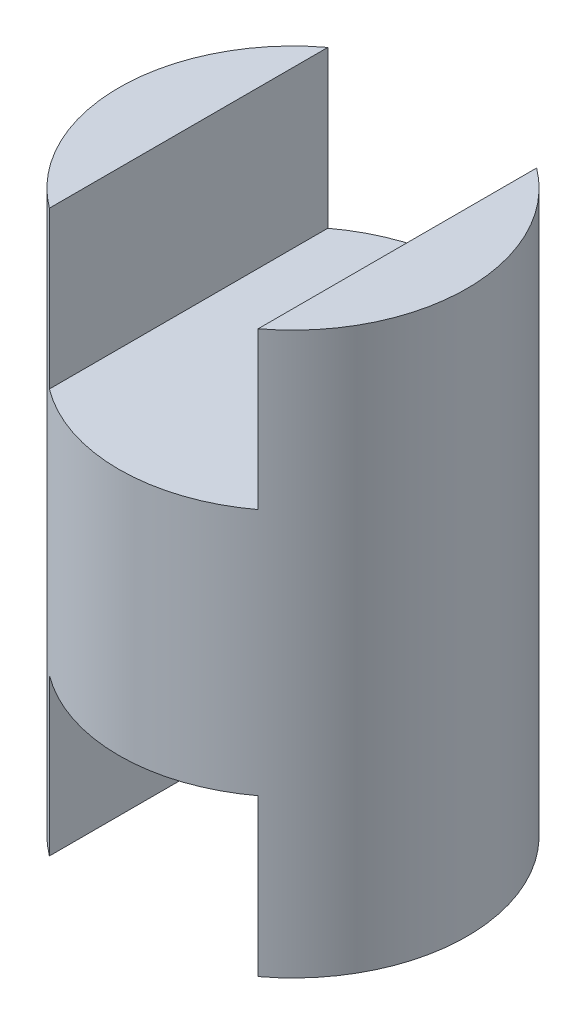
SolidWorks part; units mm, degrees
ref_plane "Front Plane" through (0, 0, 0) normal (0, 0, 1) x (1, 0, 0)
ref_plane "Top Plane" through (0, 0, 0) normal (0, 1, 0) x (1, 0, 0)
ref_plane "Right Plane" through (0, 0, 0) normal (1, 0, 0) x (0, 0, -1)
sketch "Sketch1" plane through (0, 0, 0) normal (0, 1, 0) x (1, 0, 0)
  circle A0 centre (0, 0) radius 12.7
  dimension "D1" = 25.4
extrude "Boss-Extrude1" add sketch "Sketch1" along normal blind 40.9448
sketch "Sketch2" plane through (0, 40.9448, 0) normal (0, 1, 0) x (1, 0, 0)
  line L0 (7.62, 10.16) -> (7.62, -10.16)
  line L1 (-7.62, 10.16) -> (-7.62, -10.16)
  arc A0 (-7.62, -10.16) -> (7.62, -10.16) centre (0, 0) ccw
  arc A1 (7.62, 10.16) -> (-7.62, 10.16) centre (0, 0) ccw
  dimension "D2" = 25.4
  dimension "D1" = 7.62
  dimension "D3" = 7.62
extrude "Cut-Extrude1" cut sketch "Sketch2" against normal blind 11.43
sketch "Sketch3" plane through (0, 0, 0) normal (0, -1, 0) x (1, 0, 0)
  line L1 (-7.62, 10.16) -> (-7.62, -10.16)
  line L3 (7.62, 10.16) -> (7.62, -10.16)
  arc A4 (-7.62, 10.16) -> (7.62, 10.16) centre (0, 0) cw
  arc A5 (-7.62, -10.16) -> (7.62, -10.16) centre (0, 0) ccw
  dimension "D1" = 15.24
extrude "Cut-Extrude2" cut sketch "Sketch3" against normal blind 11.43
